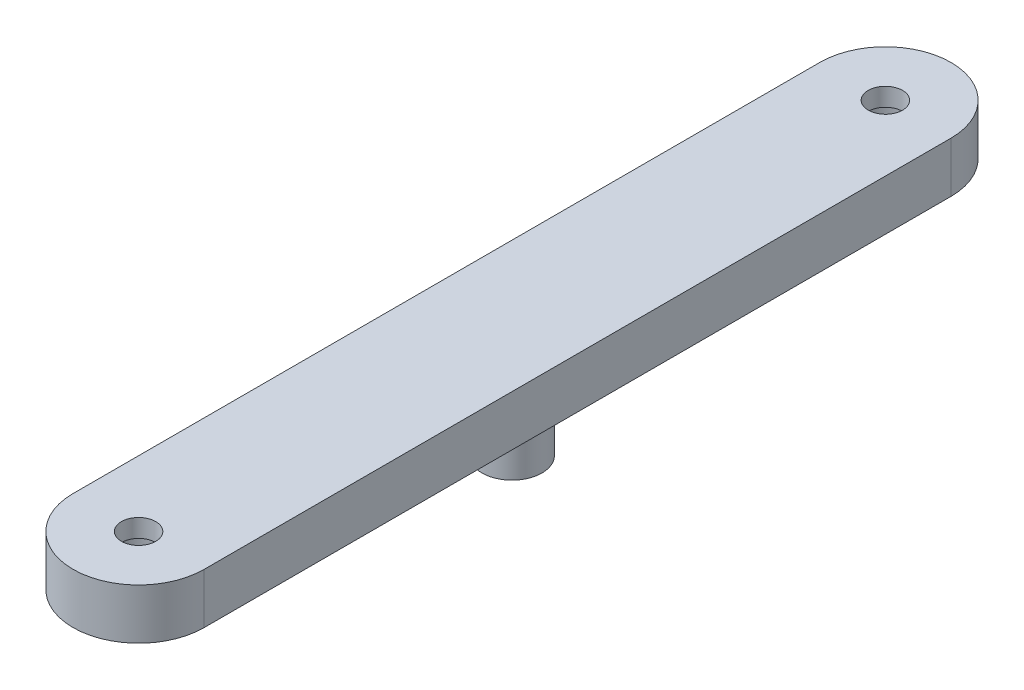
SolidWorks part; units mm, degrees
material "Aleación 6061"
ref_plane "Alzado" through (0, 0, 0) normal (0, 0, 1) x (1, 0, 0)
ref_plane "Planta" through (0, 0, 0) normal (0, 1, 0) x (1, 0, 0)
ref_plane "Vista lateral" through (0, 0, 0) normal (1, 0, 0) x (0, 0, -1)
sketch "Sk_Barra" plane through (0, 0, 0) normal (0, 1, 0) x (1, 0, 0)
  line L1 (-6.5, -207) -> (6.5, -207)
  line L2 (-6.5, -207) -> (-6.5, -133)
  line L3 (-6.5, -133) -> (6.5, -133)
  line L4 (6.5, -207) -> (6.5, -133)
  line L5 (-6.5, -207) -> (6.5, -133) construction
  line L6 (-6.5, -133) -> (6.5, -207) construction
  point P0 (0, -170)
  dimension "D1" = 13
  dimension "D2" = 74
  dimension "D3" = 170
extrude "Barra" add sketch "Sk_Barra" along normal blind 5 from offset 44.75
sketch "Sk_Extremos" plane through (0, 0, 0) normal (0, 1, 0) x (1, 0, 0)
  circle A0 centre (0, -133) radius 6.5
  circle A1 centre (0, -207) radius 6.5
  dimension "D1" = 13
  dimension "D3" = 13
  dimension "D2" = 133
  dimension "D4" = 207
extrude "Extremos" add sketch "Sk_Extremos" along normal blind 5 from offset 44.75
sketch "Sk_Perno_696" plane through (0, 0, 0) normal (0, 1, 0) x (1, 0, 0)
  circle A0 centre (0, -170) radius 2.975
  dimension "D1" = 5.95
  dimension "D2" = 170
extrude "Perno_696" add sketch "Sk_Perno_696" along normal blind 7 from offset 51.75
sketch "Sk_Pasantes_M3" plane through (0, 0, 0) normal (0, 1, 0) x (1, 0, 0)
  circle A0 centre (0, -133) radius 1.7
  circle A1 centre (0, -207) radius 1.7
  dimension "D1" = 3.4
  dimension "D3" = 3.4
  dimension "D2" = 133
  dimension "D4" = 207
extrude "Pasantes_M3" cut sketch "Sk_Pasantes_M3" along normal blind 5 from offset 44.75
sketch "Sk_Cajas_M3" plane through (0, 0, 0) normal (0, 1, 0) x (1, 0, 0)
  circle A0 centre (0, -133) radius 3
  circle A1 centre (0, -207) radius 3
  dimension "D1" = 6
  dimension "D3" = 6
  dimension "D2" = 133
  dimension "D4" = 207
extrude "Cajas_M3" cut sketch "Sk_Cajas_M3" along normal blind 3.2 from offset 44.75
